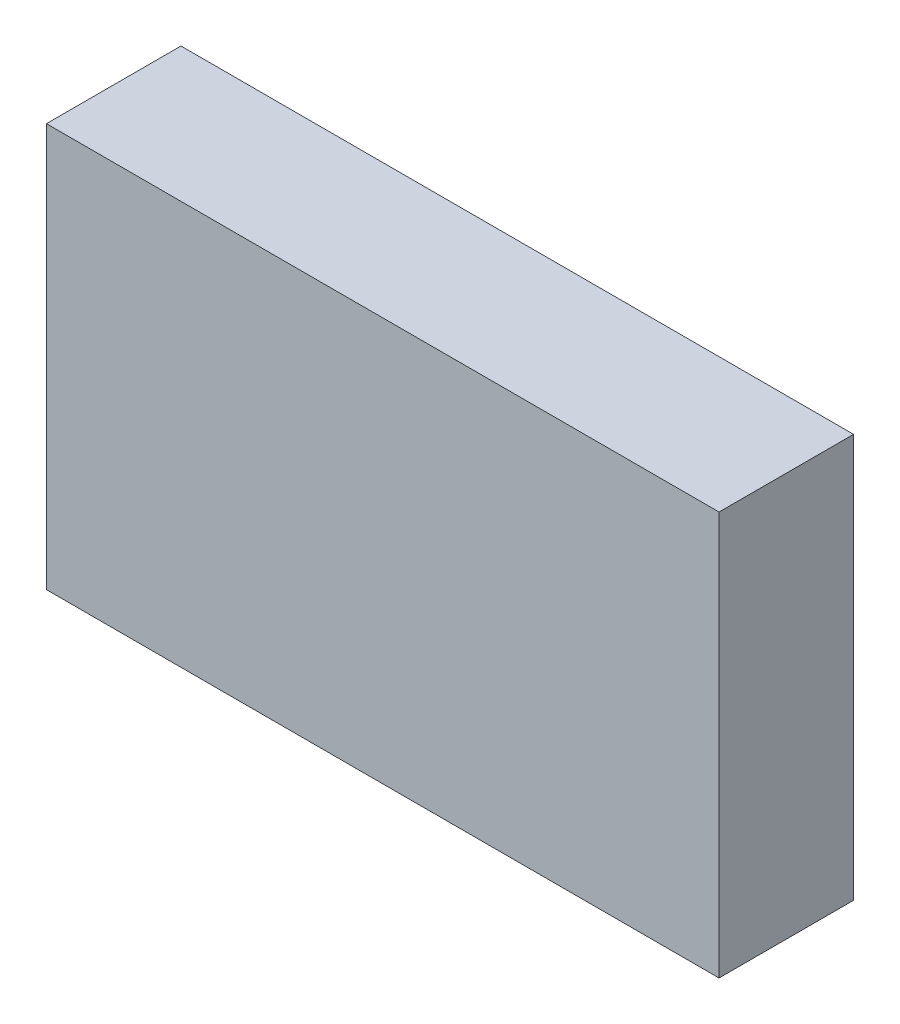
SolidWorks part; units mm, degrees
ref_plane "Спереди" through (0, 0, 0) normal (0, 0, 1) x (1, 0, 0)
ref_plane "Сверху" through (0, 0, 0) normal (0, 1, 0) x (1, 0, 0)
ref_plane "Справа" through (0, 0, 0) normal (1, 0, 0) x (0, 0, -1)
sketch "Эскиз1" plane through (0, 0, 0) normal (0, 0, 1) x (1, 0, 0)
  line L1 (-2.5, 1.5) -> (2.5, 1.5)
  line L2 (-2.5, 1.5) -> (-2.5, -1.5)
  line L3 (-2.5, -1.5) -> (2.5, -1.5)
  line L4 (2.5, 1.5) -> (2.5, -1.5)
  line L5 (-2.5, 1.5) -> (2.5, -1.5) construction
  line L6 (-2.5, -1.5) -> (2.5, 1.5) construction
  point P0 (0, 0)
  dimension "D1" = 5
  dimension "D2" = 3
extrude "Бобышка-Вытянуть1" add sketch "Эскиз1" along normal blind 1
